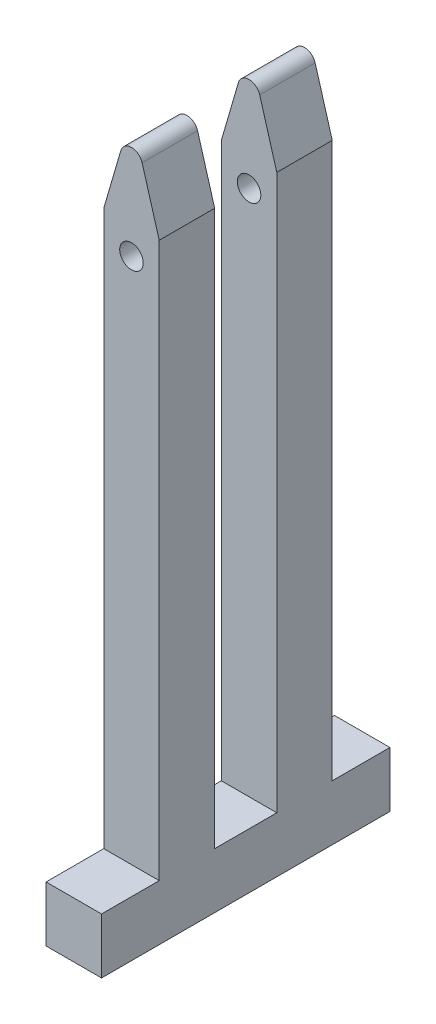
SolidWorks part; units mm, degrees
ref_plane "Front Plane" through (0, 0, 0) normal (0, 0, 1) x (1, 0, 0)
ref_plane "Top Plane" through (0, 0, 0) normal (0, 1, 0) x (1, 0, 0)
ref_plane "Right Plane" through (0, 0, 0) normal (1, 0, 0) x (0, 0, -1)
sketch "Sketch1" plane through (0, 0, 0) normal (0, 1, 0) x (1, 0, 0)
  line L0 (-1000, 0) -> (49000, 0) construction
  line L1 (-12.5, 39) -> (12.5, 39)
  line L2 (-12.5, 39) -> (-12.5, 14)
  line L3 (-12.5, 14) -> (12.5, 14)
  line L4 (12.5, 39) -> (12.5, 14)
  line L5 (-12.5, 39) -> (12.5, 14) construction
  line L6 (-12.5, 14) -> (12.5, 39) construction
  line L7 (-12.5, -14) -> (12.5, -39) construction
  line L8 (-12.5, -39) -> (12.5, -14) construction
  line L9 (12.5, -39) -> (12.5, -14)
  line L10 (-12.5, -14) -> (12.5, -14)
  line L11 (-12.5, -39) -> (-12.5, -14)
  line L12 (-12.5, -39) -> (12.5, -39)
  point P0 (0, 26.5)
  point P12 (0, -26.5)
  dimension "D1" = 25
  dimension "D2" = 25
  dimension "D3" = 14
extrude "Boss-Extrude1" add sketch "Sketch1" along normal blind 250
sketch "Sketch2" plane through (0, 0, 39) normal (0, 0, 1) x (1, 0, 0)
  line L0 (-12.5, 250) -> (12.5, 250) construction
  line L1 (-12.5, 225) -> (12.5, 225) construction
  line L2 (-12.5, 225) -> (-12.5, 250) construction
  line L3 (-12.5, 250) -> (12.5, 250) construction
  line L4 (12.5, 225) -> (12.5, 250) construction
  line L5 (-12.5, 225) -> (12.5, 250) construction
  line L6 (-12.5, 250) -> (12.5, 225) construction
  line L7 (12.5, 250) -> (12.5, 0) construction
  line L8 (-12.5, 250) -> (-12.5, 0) construction
  circle A0 centre (0, 237.5) radius 5.3
  point P0 (0, 237.5)
  dimension "D2" = 10.6
  dimension "D1" = 25
extrude "Cut-Extrude1" cut sketch "Sketch2" against normal through all
sketch "Sketch3" plane through (0, 0, 39) normal (0, 0, 1) x (1, 0, 0)
  line L0 (-12.5, 250) -> (-4.8, 276.4)
  line L1 (4.8, 276.4) -> (12.5, 250)
  line L2 (-12.5, 250) -> (12.5, 250) construction
  line L3 (-12.5, 250) -> (12.5, 250)
  arc A0 (4.8, 276.4) -> (-4.8, 276.4) centre (0, 275) ccw
  dimension "D1" = 10
  dimension "D2" = 25
extrude "Boss-Extrude2" add sketch "Sketch3" against normal up to surface (78 mm away) up to face at (5.3, 237.5, -39)
sketch "Sketch4" plane through (0, 250, 0) normal (0, -1, 0) x (1, 0, 0)
  line L1 (-12.5, 14) -> (12.5, 14)
  line L2 (-12.5, 14) -> (-12.5, -14)
  line L3 (-12.5, -14) -> (12.5, -14)
  line L4 (12.5, 14) -> (12.5, -14)
extrude "Cut-Extrude2" cut sketch "Sketch4" against normal through all
sketch "Sketch5" plane through (0, 0, -39) normal (0, 0, -1) x (-1, 0, 0)
  circle A1 centre (0, 275) radius 5
  dimension "D1" = 10
extrude "Boss-Extrude3" add sketch "Sketch5" against normal up to surface (78 mm away)
sketch "Sketch6" plane through (0, 0, 0) normal (0, -1, 0) x (1, 0, 0)
  line L1 (-12.5, -65) -> (12.5, -65)
  line L2 (-12.5, -65) -> (-12.5, 65)
  line L3 (-12.5, 65) -> (12.5, 65)
  line L4 (12.5, -65) -> (12.5, 65)
  line L5 (-12.5, -65) -> (12.5, 65) construction
  line L6 (-12.5, 65) -> (12.5, -65) construction
  point P0 (0, 0)
  dimension "D1" = 25
  dimension "D2" = 130
extrude "Boss-Extrude4" add sketch "Sketch6" along normal blind 25
sketch "Sketch7" plane through (0, 0, 0) normal (0, 1, 0) x (1, 0, 0)
  line L1 (-12.5, -14) -> (12.5, -14)
  line L2 (-12.5, -14) -> (-12.5, 14)
  line L3 (-12.5, 14) -> (12.5, 14)
  line L4 (12.5, -14) -> (12.5, 14)
extrude "Cut-Extrude3" cut sketch "Sketch7" along normal blind 323
